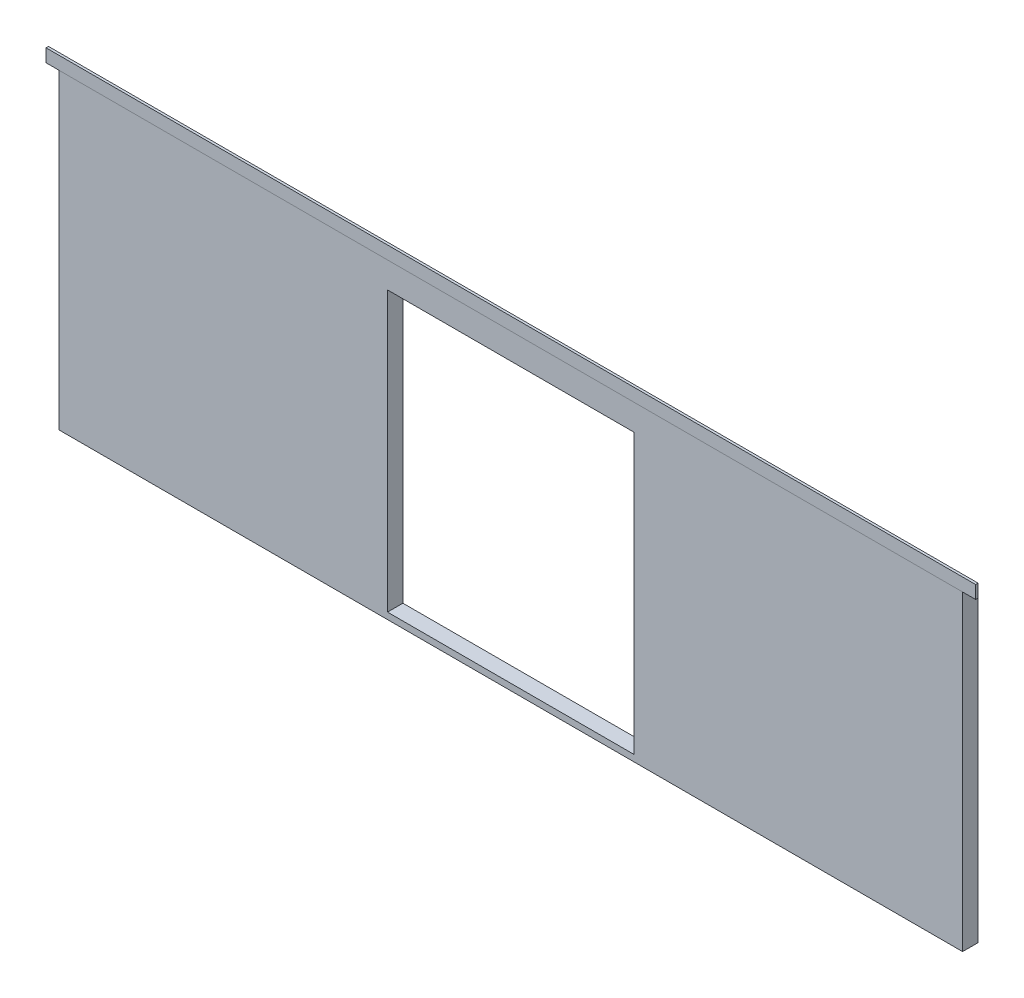
SolidWorks part; units mm, degrees
ref_plane "Front Plane" through (0, 0, 0) normal (0, 0, 1) x (1, 0, 0)
ref_plane "Top Plane" through (0, 0, 0) normal (0, 1, 0) x (1, 0, 0)
ref_plane "Right Plane" through (0, 0, 0) normal (1, 0, 0) x (0, 0, -1)
sketch "Sketch1" plane through (0, 0, 0) normal (0, 0, 1) x (1, 0, 0)
  line L0 (0, 0) -> (3536.95, 0)
  line L1 (3536.95, 0) -> (3536.95, 2438.4)
  line L2 (3536.95, 2438.4) -> (-3536.95, 2438.4)
  line L3 (-3536.95, 2438.4) -> (-3536.95, 0)
  line L4 (-3536.95, 0) -> (0, 0)
  line L5 (25.4, 2387.6) -> (25.4, 50.8)
  line L6 (-25.4, 2387.6) -> (-25.4, 50.8)
  line L7 (431.8, 2387.6) -> (431.8, 50.8)
  line L8 (381, 2387.6) -> (381, 50.8)
  line L9 (838.2, 2387.6) -> (838.2, 50.8)
  line L10 (-3486.15, 2387.6) -> (-3203.575, 2387.6)
  line L11 (-3486.15, 2387.6) -> (-3486.15, 50.8)
  line L12 (-3486.15, 50.8) -> (-3203.575, 50.8)
  line L13 (3486.15, 2387.6) -> (3486.15, 50.8)
  line L14 (787.4, 2387.6) -> (787.4, 50.8)
  line L15 (1244.6, 2387.6) -> (1244.6, 50.8)
  line L16 (1193.8, 2387.6) -> (1193.8, 50.8)
  line L17 (1651, 2387.6) -> (1651, 50.8)
  line L18 (1600.2, 2387.6) -> (1600.2, 50.8)
  line L19 (2057.4, 2387.6) -> (2057.4, 50.8)
  line L20 (2006.6, 2387.6) -> (2006.6, 50.8)
  line L21 (2463.8, 2387.6) -> (2463.8, 50.8)
  line L22 (2413, 2387.6) -> (2413, 50.8)
  line L23 (2870.2, 2387.6) -> (2870.2, 50.8)
  line L24 (2819.4, 2387.6) -> (2819.4, 50.8)
  line L25 (2870.2, 50.8) -> (3152.775, 50.8)
  line L26 (2463.8, 50.8) -> (2819.4, 50.8)
  line L27 (-381, 2387.6) -> (-381, 50.8)
  line L28 (-431.8, 2387.6) -> (-431.8, 50.8)
  line L29 (-787.4, 2387.6) -> (-787.4, 50.8)
  line L30 (-838.2, 2387.6) -> (-838.2, 50.8)
  line L31 (-1193.8, 2387.6) -> (-1193.8, 50.8)
  line L32 (-1244.6, 2387.6) -> (-1244.6, 50.8)
  line L33 (-1600.2, 2387.6) -> (-1600.2, 50.8)
  line L34 (-1651, 2387.6) -> (-1651, 50.8)
  line L35 (-2006.6, 2387.6) -> (-2006.6, 50.8)
  line L36 (-2057.4, 2387.6) -> (-2057.4, 50.8)
  line L37 (-2413, 2387.6) -> (-2413, 50.8)
  line L38 (-2463.8, 2387.6) -> (-2463.8, 50.8)
  line L39 (-2819.4, 2387.6) -> (-2819.4, 50.8)
  line L40 (-2870.2, 2387.6) -> (-2870.2, 50.8)
  line L41 (-2819.4, 2387.6) -> (-2463.8, 2387.6)
  line L42 (-2413, 2387.6) -> (-2057.4, 2387.6)
  line L43 (-3276.6, 2387.6) -> (-3276.6, 50.8) [skipped]
  line L44 (-3225.8, 2387.6) -> (-3225.8, 50.8) [skipped]
  line L45 (-2006.6, 2387.6) -> (-1651, 2387.6)
  line L46 (-1600.2, 2387.6) -> (-1244.6, 2387.6)
  line L47 (-1193.8, 2387.6) -> (-838.2, 2387.6)
  line L48 (-787.4, 2387.6) -> (-431.8, 2387.6)
  line L49 (-381, 2387.6) -> (-25.4, 2387.6)
  line L50 (25.4, 2387.6) -> (381, 2387.6)
  line L51 (431.8, 2387.6) -> (787.4, 2387.6)
  line L52 (838.2, 2387.6) -> (1193.8, 2387.6)
  line L53 (1244.6, 2387.6) -> (1600.2, 2387.6)
  line L54 (1651, 2387.6) -> (2006.6, 2387.6)
  line L55 (2057.4, 2387.6) -> (2413, 2387.6)
  line L56 (2463.8, 2387.6) -> (2819.4, 2387.6)
  line L57 (2870.2, 2387.6) -> (3152.775, 2387.6)
  line L58 (3276.6, 2387.6) -> (3276.6, 50.8) [skipped]
  line L59 (3225.8, 2387.6) -> (3225.8, 50.8) [skipped]
  line L60 (2057.4, 50.8) -> (2413, 50.8)
  line L61 (1651, 50.8) -> (2006.6, 50.8)
  line L62 (1244.6, 50.8) -> (1600.2, 50.8)
  line L63 (838.2, 50.8) -> (1193.8, 50.8)
  line L64 (431.8, 50.8) -> (787.4, 50.8)
  line L65 (25.4, 50.8) -> (381, 50.8)
  line L66 (-381, 50.8) -> (-25.4, 50.8)
  line L67 (-787.4, 50.8) -> (-431.8, 50.8)
  line L68 (-1193.8, 50.8) -> (-838.2, 50.8)
  line L69 (-1600.2, 50.8) -> (-1244.6, 50.8)
  line L70 (-2006.6, 50.8) -> (-1651, 50.8)
  line L71 (-2413, 50.8) -> (-2057.4, 50.8)
  line L72 (-2819.4, 50.8) -> (-2463.8, 50.8)
  line L73 (-3152.775, 50.8) -> (-3152.775, 2387.6)
  line L74 (-3203.575, 2387.6) -> (-3203.575, 50.8)
  line L75 (-3152.775, 2387.6) -> (-2870.2, 2387.6)
  line L76 (-3152.775, 50.8) -> (-2870.2, 50.8)
  line L77 (3203.575, 2387.6) -> (3203.575, 50.8)
  line L78 (3152.775, 50.8) -> (3152.775, 2387.6)
  line L79 (3203.575, 2387.6) -> (3486.15, 2387.6)
  line L80 (3203.575, 50.8) -> (3486.15, 50.8)
  dimension "D1" = 9
  dimension "D2" = 9
extrude "Boss-Extrude1" add sketch "Sketch1" along normal blind 101.6
sketch "Sketch2" plane through (0, 0, 101.6) normal (0, 0, 1) x (1, 0, 0)
  line L8 (-3536.95, 2438.4) -> (3536.95, 2438.4)
  line L9 (-3536.95, 2438.4) -> (-3536.95, 0)
  line L10 (-3536.95, 0) -> (3536.95, 0)
  line L11 (3536.95, 2438.4) -> (3536.95, 0)
extrude "Boss-Extrude2" add sketch "Sketch2" along normal blind 19.05
sketch "Sketch3" plane through (0, 0, 120.65) normal (0, 0, 1) x (1, 0, 0)
  line L1 (0, 2235.2) -> (965.2, 2235.2)
  line L2 (965.2, 2235.2) -> (965.2, 50.8)
  line L3 (838.2, 50.8) -> (1193.8, 50.8) construction
  line L4 (965.2, 50.8) -> (-965.2, 50.8)
  line L5 (-381, 50.8) -> (-25.4, 50.8) construction
  line L6 (-965.2, 50.8) -> (-965.2, 2235.2)
  line L7 (-965.2, 2235.2) -> (0, 2235.2)
extrude "Cut-Extrude1" cut sketch "Sketch3" against normal through all
sketch "Sketch4" plane through (0, 0, 101.6) normal (0, 0, -1) x (-1, 0, 0)
  line L0 (-965.2, 2336.8) -> (-965.2, 2387.6)
  line L1 (-1193.8, 2387.6) -> (-838.2, 2387.6) construction
  line L2 (-965.2, 2387.6) -> (-1066.8, 2387.6)
  line L3 (-1066.8, 2387.6) -> (-1066.8, 50.8)
  line L4 (1193.8, 50.8) -> (-1193.8, 50.8) construction
  line L5 (-1066.8, 50.8) -> (-965.2, 50.8)
  line L6 (965.2, 2336.8) -> (965.2, 2387.6)
  line L7 (838.2, 2387.6) -> (1193.8, 2387.6) construction
  line L8 (965.2, 2387.6) -> (1066.8, 2387.6)
  line L9 (1066.8, 2387.6) -> (1066.8, 50.8)
  line L10 (1066.8, 50.8) -> (965.2, 50.8)
  line L11 (-381, 2235.2) -> (-381, 2387.6) construction
  line L13 (-787.4, 2336.8) -> (-431.8, 2336.8)
  line L14 (-787.4, 2235.2) -> (-787.4, 2387.6) construction
  line L15 (-431.8, 2387.6) -> (-431.8, 2235.2) construction
  line L16 (-431.8, 2336.8) -> (-431.8, 2235.2)
  line L17 (-431.8, 2235.2) -> (-787.4, 2235.2)
  line L18 (-787.4, 2235.2) -> (-787.4, 2336.8)
  line L19 (-381, 2336.8) -> (-25.4, 2336.8)
  line L20 (-381, 2336.8) -> (-381, 2235.2)
  line L21 (-381, 2235.2) -> (-25.4, 2235.2)
  line L22 (-25.4, 2336.8) -> (-25.4, 2235.2)
  line L23 (25.4, 2235.2) -> (25.4, 2387.6) construction
  line L24 (25.4, 2336.8) -> (381, 2336.8)
  line L25 (25.4, 2336.8) -> (25.4, 2235.2)
  line L26 (25.4, 2235.2) -> (381, 2235.2)
  line L27 (381, 2336.8) -> (381, 2235.2)
  line L28 (431.8, 2235.2) -> (431.8, 2387.6) construction
  line L29 (431.8, 2336.8) -> (787.4, 2336.8)
  line L30 (431.8, 2336.8) -> (431.8, 2235.2)
  line L31 (431.8, 2235.2) -> (787.4, 2235.2)
  line L32 (787.4, 2336.8) -> (787.4, 2235.2)
  line L33 (431.8, 2235.2) -> (787.4, 2235.2) construction
  line L34 (787.4, 2387.6) -> (787.4, 2235.2) construction
  line L35 (838.2, 2235.2) -> (838.2, 2387.6) construction
  line L36 (838.2, 2336.8) -> (965.2, 2336.8)
  line L37 (838.2, 2336.8) -> (838.2, 2235.2)
  line L38 (838.2, 2235.2) -> (965.2, 2235.2)
  line L40 (-838.2, 2387.6) -> (-838.2, 2235.2) construction
  line L41 (-838.2, 2336.8) -> (-965.2, 2336.8)
  line L42 (-838.2, 2336.8) -> (-838.2, 2235.2)
  line L43 (-838.2, 2235.2) -> (-965.2, 2235.2)
  line L45 (-965.2, 50.8) -> (-965.2, 2235.2)
  line L46 (965.2, 50.8) -> (965.2, 2235.2)
extrude "Boss-Extrude3" add sketch "Sketch4" along normal blind 101.6
sketch "Sketch5" plane through (0, 0, 120.65) normal (0, 0, 1) x (1, 0, 0)
  line L0 (-3536.95, 2438.4) -> (-3638.55, 2438.4)
  line L1 (-3638.55, 2438.4) -> (-3638.55, 2540)
  line L2 (3536.95, 2438.4) -> (3638.55, 2438.4)
  line L3 (3638.55, 2438.4) -> (3638.55, 2540)
  line L4 (3638.55, 2540) -> (-3638.55, 2540)
  line L5 (-3536.95, 2438.4) -> (3536.95, 2438.4)
extrude "Boss-Extrude5" add sketch "Sketch5" against normal blind 19.05 separate body
